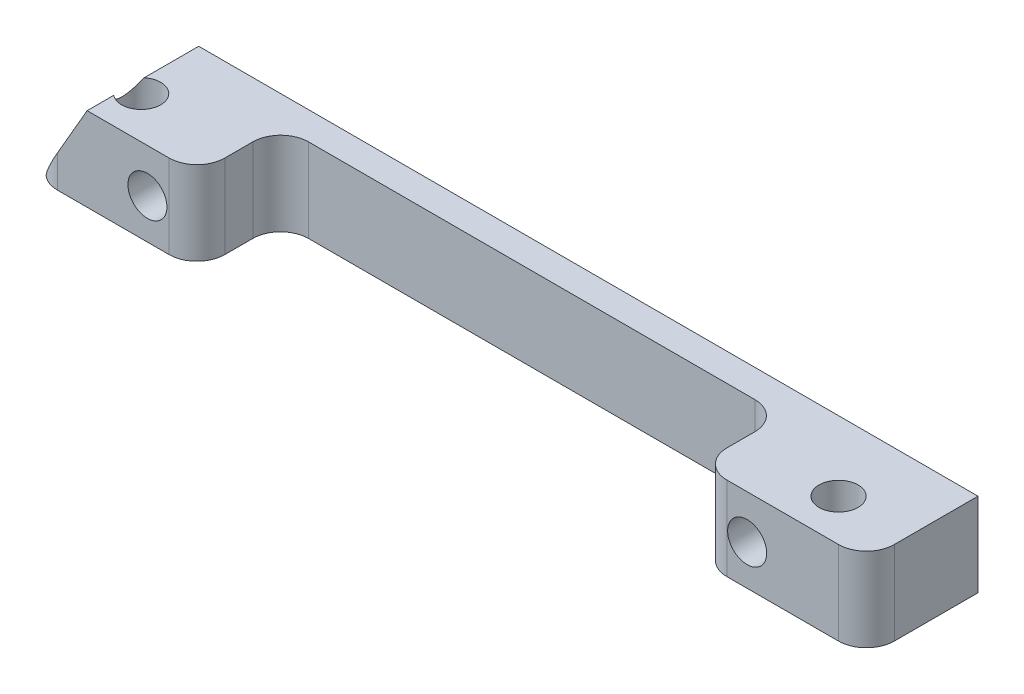
SolidWorks part; units mm, degrees
material "Nylon 6/10"
ref_plane "Front Plane" through (0, 0, 0) normal (0, 0, 1) x (1, 0, 0)
ref_plane "Top Plane" through (0, 0, 0) normal (0, 1, 0) x (1, 0, 0)
ref_plane "Right Plane" through (0, 0, 0) normal (1, 0, 0) x (0, 0, -1)
sketch "Sketch1" plane through (0, 0, 0) normal (0, 0, 1) x (1, 0, 0)
  line L1 (-30, 3) -> (30, 3)
  line L3 (-30, -3) -> (30, -3)
  line L4 (30, 3) -> (30, -3)
  line L5 (0, 0) -> (0, 3) construction
  line L6 (0, 0) -> (30, 0) construction
  line L9 (-30, 3) -> (-30, -3)
  line L11 (-30, -3.138) -> (-30, -5.76) construction
  line L12 (-30, -3.138) -> (-30, -5.76) construction
  line L13 (30, -3.138) -> (30, -5.76) construction
  line L14 (30, -3.138) -> (30, -5.76) construction
  point P0 (0, 0)
  dimension "D1" = 6
extrude "Base" add sketch "Sketch1" along normal blind 2
sketch "Sketch2" plane through (0, 0, 0) normal (0, 0, 1) x (1, 0, 0)
  line L0 (-17.8654, 16.8738) -> (-38.65, -19.1262) construction
  line L1 (-25.8754, 3) -> (-29.3395, -3)
  line L2 (30, 3) -> (-30, 3) construction
  line L3 (-25.8754, 3) -> (-30, 3)
  line L4 (-30, 3) -> (-30, -3) construction
  line L5 (-30, 3) -> (-30, -3)
  line L6 (-30, -3) -> (30, -3) construction
  line L7 (-30, -3) -> (-29.3395, -3)
sketch "Sketch4" plane through (0, -3, 0) normal (0, 1, 0) x (1, 0, 0)
  line L0 (-30, -2) -> (30, -2) construction
  line L1 (-30, -2) -> (-18, -2)
  line L2 (30, -2) -> (30, -8)
  line L5 (-30, -2) -> (-30, -8)
  line L8 (25, -5) -> (25, -8) construction
  line L9 (-25, -5) -> (-25, -8) construction
  line L10 (18, -2) -> (30, -2)
  line L11 (-30, -8) -> (-25, -8)
  line L12 (-25, -8) -> (-18, -8)
  line L13 (-18, -8) -> (-18, -2)
  line L14 (30, -8) -> (25, -8)
  line L15 (25, -8) -> (18, -8)
  line L16 (18, -8) -> (18, -2)
  circle A0 centre (25, -5) radius 2.15 construction
  circle A1 centre (25, -5) radius 2.15 construction
  circle A2 centre (-25, -5) radius 2.15 construction
  circle A3 centre (-25, -5) radius 2.15 construction
  dimension "D1" = 6
  dimension "D2" = 12
extrude "Boss-Extrude2" add sketch "Sketch4" along normal up to surface (6 mm away) up to face at (0, 3, 1)
fillet "Fillet1" radius 2 6 edges at (30, 0, 8) (-30, 0, 8) (-18, 0, 8) (18, 0, 8) (-18, 0, 2) (18, 0, 2)
extrude "Crop" cut sketch "Sketch2" along normal up to next
sketch "Sketch5" plane through (0, -3, 0) normal (0, -1, 0) x (1, 0, 0)
  circle A0 centre (25, 5) radius 1.4
  circle A1 centre (-25, 5) radius 1.4
  dimension "D1" = 2.8
extrude "Fan screws" cut sketch "Sketch5" against normal up to next
sketch "Sketch3" plane through (0, 0, 0) normal (0, 0, 1) x (1, 0, 0)
  circle A0 centre (-21.552, -0.1262) radius 1.75 construction
  circle A1 centre (21.448, -0.1262) radius 1.75 construction
  circle A2 centre (-21.552, -0.1262) radius 1.75 construction
  circle A3 centre (21.448, -0.1262) radius 1.75 construction
  circle A4 centre (21.448, -0.1262) radius 1.4
  circle A5 centre (-21.552, -0.1262) radius 1.4
  dimension "D1" = 2.8
extrude "PCB screws" cut sketch "Sketch3" along normal up to next
